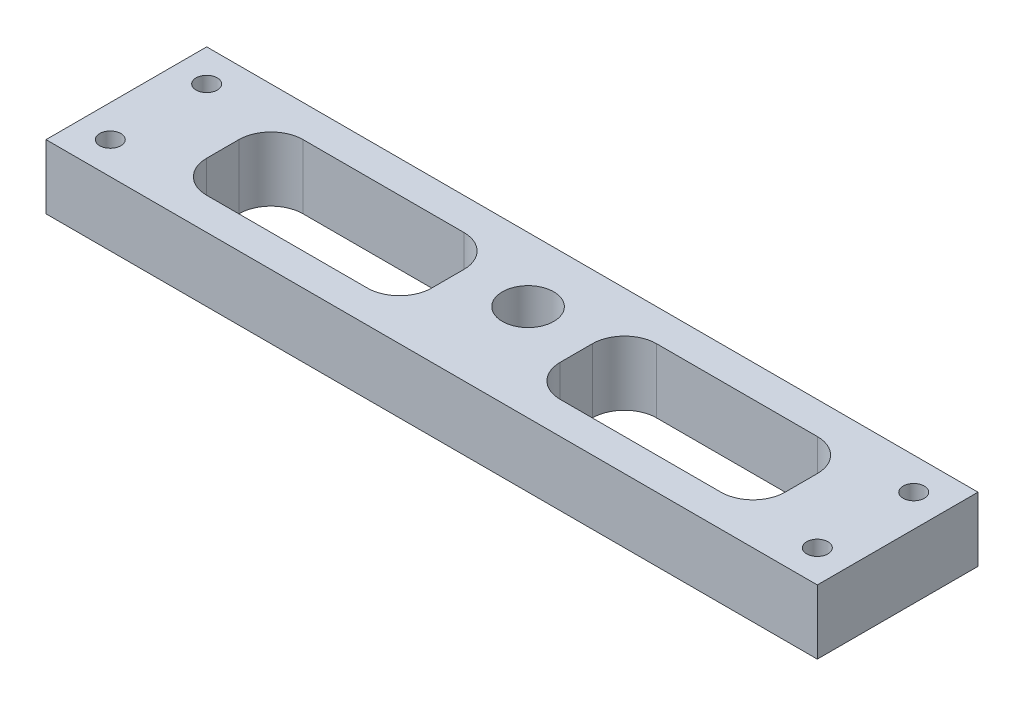
SolidWorks part; units mm, degrees
material "6063-T83"
ref_plane "Front Plane" through (0, 0, 0) normal (0, 0, 1) x (1, 0, 0)
ref_plane "Top Plane" through (0, 0, 0) normal (0, 1, 0) x (1, 0, 0)
ref_plane "Right Plane" through (0, 0, 0) normal (1, 0, 0) x (0, 0, -1)
sketch "Sketch1" plane through (0, 0, 0) normal (0, 1, 0) x (1, 0, 0)
  line L0 (-110, 0) -> (-10, -20) construction
  line L1 (0, 0) -> (-120, 0)
  line L2 (0, 0) -> (0, -25)
  line L3 (0, -25) -> (-120, -25)
  line L4 (-120, 0) -> (-120, -25)
  line L7 (-120, -3) -> (-120, -22) construction
  line L8 (0, -25) -> (-10, -25) construction
  line L9 (-110, 1.3485) -> (-110, -22) construction
  line L10 (-105, -5) -> (-70, -5)
  line L11 (-105, -5) -> (-105, -20)
  line L12 (-105, -20) -> (-70, -20)
  line L13 (-70, -5) -> (-70, -20)
  line L14 (-15, -5) -> (-50, -5)
  line L15 (-15, -5) -> (-15, -20)
  line L16 (-15, -20) -> (-50, -20)
  line L17 (-50, -5) -> (-50, -20)
  line L18 (-10, 1.3485) -> (-10, -22) construction
  circle A0 centre (-60, -10) radius 4
  dimension "D3" = 8
  dimension "D6" = 10
  dimension "D1" = 5
  dimension "D2" = 5
  dimension "D4" = 5
  dimension "D5" = 5
  dimension "D7" = 10
extrude "Boss-Extrude1" add sketch "Sketch1" along normal blind 10
fillet "Fillet1" radius 5 8 edges at (-15, 5, 20) (-15, 5, 5) (-50, 5, 20) (-50, 5, 5) (-105, 5, 5) (-105, 5, 20) (-70, 5, 5) (-70, 5, 20)
hole_wizard "M4x0.7 Tapped Hole1" positions "Sketch2" profile "Sketch3" tap size "M4x0.7" standard "ANSI Metric" end condition through all
sketch "Sketch2" plane through (0, 10, 0) normal (0, 1, 0) x (1, 0, 0)
  line L0 (-115, 0) -> (-115, -5) construction
  line L1 (0, 0) -> (-120, 0) construction
  line L2 (-115, -5) -> (-120, -5) construction
  line L3 (-120, 0) -> (-120, -25) construction
  line L5 (-120, -20) -> (-115, -20) construction
  line L6 (-115, -20) -> (-115, -25) construction
  line L7 (-120, -25) -> (0, -25) construction
  line L10 (-5, -25) -> (-5, -20) construction
  line L11 (-5, -20) -> (0, -20) construction
  line L12 (0, -25) -> (0, 0) construction
  line L15 (0, -5) -> (-5, -5) construction
  line L16 (-5, -5) -> (-5, 0) construction
  point P0 (-115, -5)
  point P2 (-115, -20)
  point P4 (-5, -5)
  point P6 (-5, -20)
  dimension "D1" = 5
sketch "Sketch3" plane through (-115, 10, 5) normal (1, 0, 0) x (0, 0, 1)
  line L0 (0, 0) -> (0, 10)
  line L1 (0, 10) -> (1.65, 10)
  line L2 (1.65, 10) -> (1.65, 0)
  line L5 (1.65, 0) -> (0, 0)
  line L11 (0, -6.35) -> (0, 107.95) construction
  dimension "Thru Tap Drill Dia." = 3.3
  dimension "Thru Tap Drill Depth" = 10
cosmetic thread "Hole Thread1" parameters "D2"=4
cosmetic thread "Hole Thread2" parameters "D2"=4
cosmetic thread "Hole Thread3" parameters "D2"=4
cosmetic thread "Hole Thread4" parameters "D2"=4
